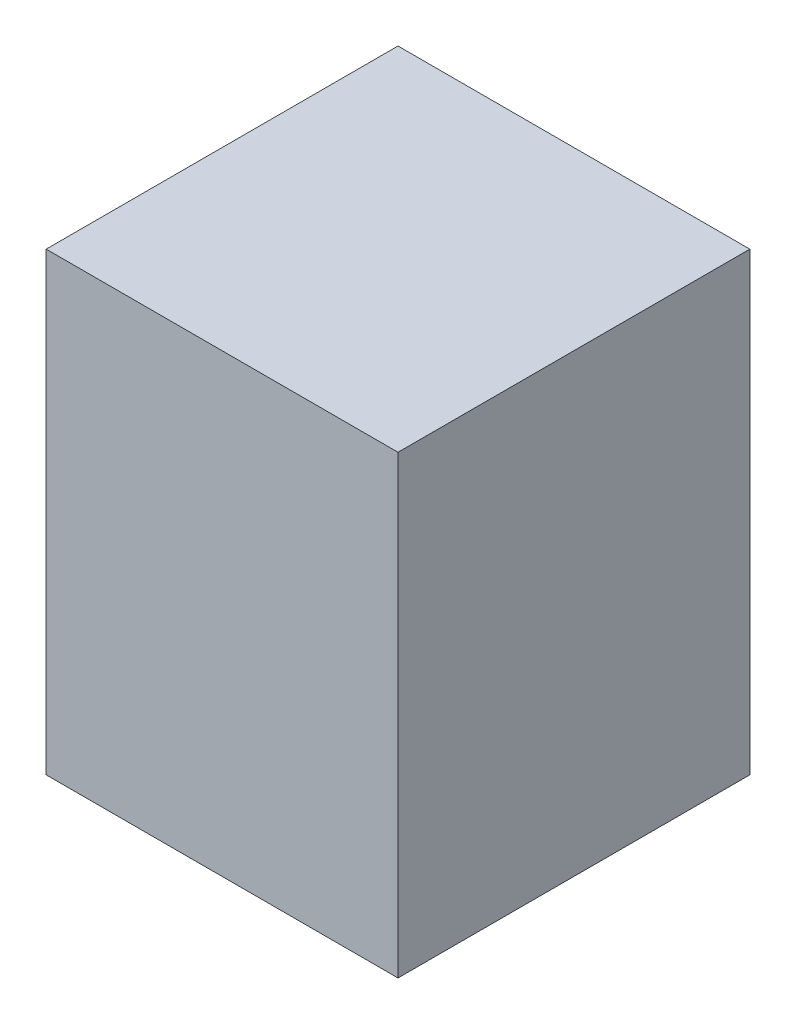
SolidWorks part; units mm, degrees
ref_plane "Front" through (0, 0, 0) normal (0, 0, 1) x (1, 0, 0)
ref_plane "Top" through (0, 0, 0) normal (0, 1, 0) x (1, 0, 0)
ref_plane "Right" through (0, 0, 0) normal (1, 0, 0) x (0, 0, -1)
sketch "Sketch1" plane through (0, 0, 0) normal (0, 1, 0) x (1, 0, 0)
  line L1 (-2590.8, -2590.8) -> (2590.8, -2590.8)
  line L2 (-2590.8, -2590.8) -> (-2590.8, 2590.8)
  line L3 (-2590.8, 2590.8) -> (2590.8, 2590.8)
  line L4 (2590.8, -2590.8) -> (2590.8, 2590.8)
  line L5 (-2590.8, -2590.8) -> (2590.8, 2590.8) construction
  line L6 (-2590.8, 2590.8) -> (2590.8, -2590.8) construction
  point P0 (0, 0)
  dimension "D1" = 5181.6
extrude "Boss-Extrude1" add sketch "Sketch1" along normal blind 6705.6
shell "Shell1" thickness 304.8
